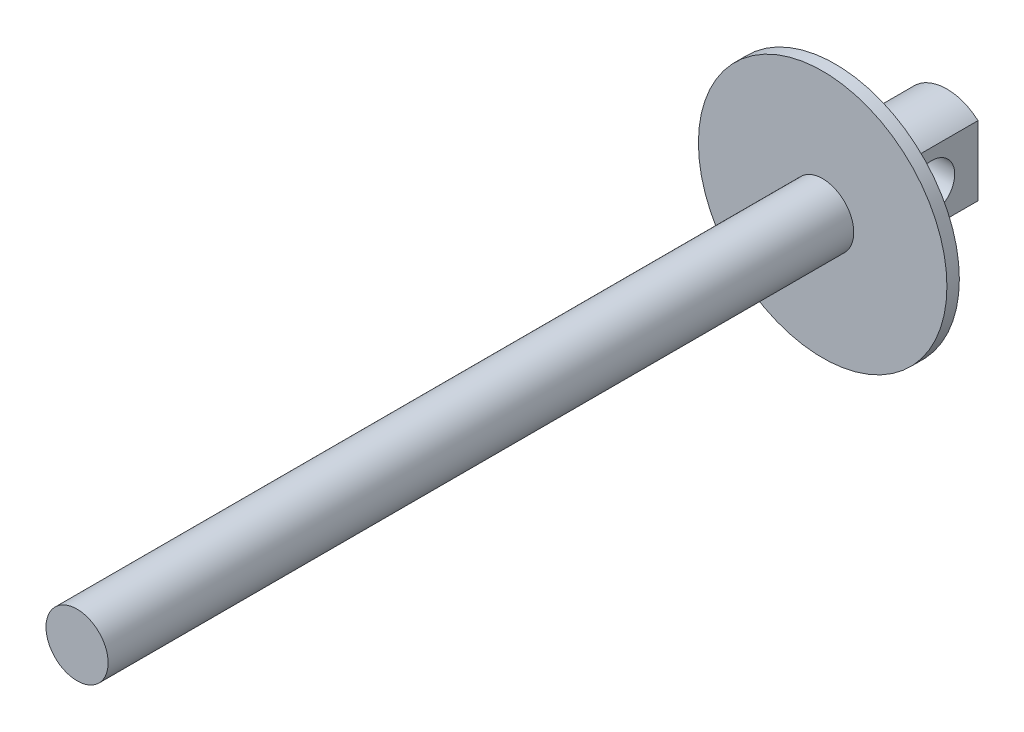
SolidWorks part; units mm, degrees
ref_plane "Front Plane" through (0, 0, 0) normal (0, 0, 1) x (1, 0, 0)
ref_plane "Top Plane" through (0, 0, 0) normal (0, 1, 0) x (1, 0, 0)
ref_plane "Right Plane" through (0, 0, 0) normal (1, 0, 0) x (0, 0, -1)
sketch "Sketch1" plane through (0, 0, 0) normal (0, 0, 1) x (1, 0, 0)
  circle A0 centre (0, 0) radius 25.4
  dimension "D1" = 50.8
extrude "Boss-Extrude1" add sketch "Sketch1" along normal blind 2.54
sketch "Sketch2" plane through (0, 0, 2.54) normal (0, 0, 1) x (1, 0, 0)
  circle A0 centre (0, 0) radius 6.35
  dimension "D1" = 12.7
extrude "Boss-Extrude2" add sketch "Sketch2" along normal blind 152.4
sketch "Sketch3" plane through (0, 0, 0) normal (0, 0, -1) x (-1, 0, 0)
  circle A0 centre (0, 0) radius 9.525
  dimension "D1" = 19.05
extrude "Boss-Extrude3" add sketch "Sketch3" along normal blind 22.86
sketch "Sketch4" plane through (0, 0, 0) normal (0, 1, 0) x (1, 0, 0)
  line L0 (0, -27.94) -> (0, 27.94) construction
  line L1 (9.525, 22.86) -> (6.35, 22.86)
  line L2 (9.525, 22.86) -> (9.525, 3.81)
  line L3 (9.525, 3.81) -> (6.35, 3.81)
  line L4 (6.35, 22.86) -> (6.35, 3.81)
  line L5 (-9.525, 22.86) -> (-6.35, 22.86)
  line L6 (-9.525, 22.86) -> (-9.525, 3.81)
  line L7 (-9.525, 3.81) -> (-6.35, 3.81)
  line L8 (-6.35, 22.86) -> (-6.35, 3.81)
  dimension "D1" = 19.05
  dimension "D2" = 19.05
  dimension "D3" = 6.35
  dimension "D4" = 6.35
extrude "Cut-Extrude2" cut sketch "Sketch4" against normal through all both and the other way through all
sketch "Sketch5" plane through (-6.35, 0, 0) normal (-1, 0, 0) x (0, 0, 1)
  line L0 (27.94, 0) -> (-27.94, 0) construction
  line L1 (-22.86, 7.0995) -> (-22.86, -7.0995) construction
  circle A0 centre (-13.335, 0) radius 4.7625
  dimension "D1" = 9.525
  dimension "D2" = 9.525
extrude "Cut-Extrude3" cut sketch "Sketch5" against normal through all both
equation "\"D2@Sketch4\"=\"D1@Sketch4\""
equation "\"D4@Sketch4\"=\"D3@Sketch4\""
